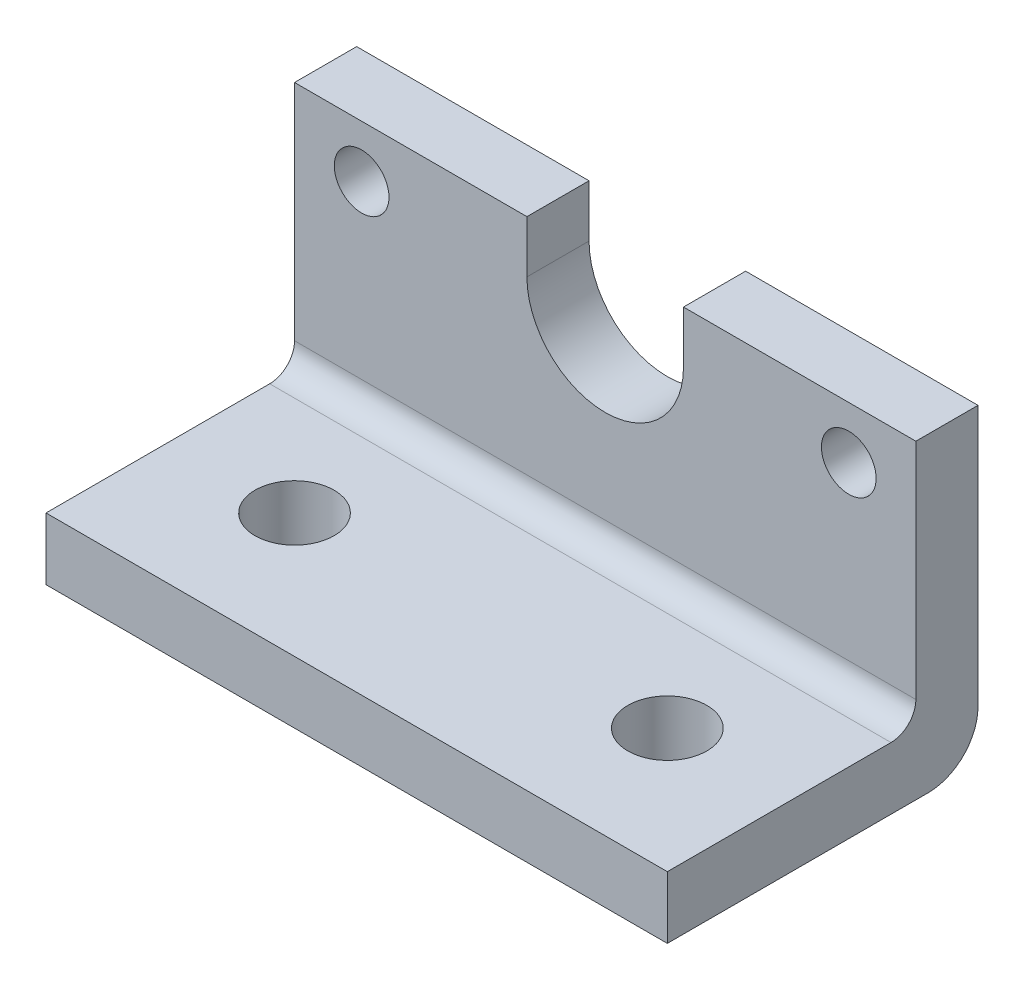
SolidWorks part; units mm, degrees
ref_plane "Front Plane" through (0, 0, 0) normal (0, 0, 1) x (1, 0, 0)
ref_plane "Top Plane" through (0, 0, 0) normal (0, 1, 0) x (1, 0, 0)
ref_plane "Right Plane" through (0, 0, 0) normal (1, 0, 0) x (0, 0, -1)
sketch "Sketch1" plane through (0, 0, 0) normal (0, 0, 1) x (1, 0, 0)
  line L0 (-4.0005, 13.208) -> (-4.0005, 15.875)
  line L1 (-15.875, 15.875) -> (-4.0005, 15.875)
  line L2 (-15.875, 15.875) -> (-15.875, 0)
  line L3 (-15.875, 0) -> (15.875, 0)
  line L4 (15.875, 15.875) -> (15.875, 0)
  line L5 (-15.875, 15.875) -> (15.875, 0) construction
  line L6 (-15.875, 0) -> (15.875, 15.875) construction
  line L7 (4.0005, 13.208) -> (4.0005, 15.875)
  line L8 (0, 13.208) -> (0, 23.3212) construction
  line L9 (4.0005, 15.875) -> (15.875, 15.875)
  arc A0 (-4.0005, 13.208) -> (4.0005, 13.208) centre (0, 13.208) ccw
  circle A1 centre (12.446, 13.208) radius 1.397
  circle A2 centre (-12.446, 13.208) radius 1.397
  point P0 (0, 7.9375)
  dimension "D3" = 8.001
  dimension "D5" = 2.794
  dimension "D1" = 31.75
  dimension "D2" = 15.875
  dimension "D4" = 13.208
  dimension "D6" = 24.892
extrude "Boss-Extrude1" add sketch "Sketch1" against normal blind 3.175
sketch "Sketch2" plane through (0, 0, 0) normal (0, 1, 0) x (1, 0, 0)
  line L0 (0, -12.7) -> (0, 0) construction
  line L1 (-15.875, -12.7) -> (15.875, -12.7)
  line L2 (-15.875, -12.7) -> (-15.875, 0)
  line L3 (-15.875, 0) -> (15.875, 0)
  line L4 (15.875, -12.7) -> (15.875, 0)
  line L5 (-15.875, -12.7) -> (15.875, 0) construction
  line L6 (-15.875, 0) -> (15.875, -12.7) construction
  circle A0 centre (-9.525, -6.35) radius 2.0193
  circle A1 centre (9.525, -6.35) radius 2.0193
  point P0 (0, -6.35)
  dimension "D2" = 4.0386
  dimension "D1" = 12.7
  dimension "D3" = 19.05
extrude "Boss-Extrude2" add sketch "Sketch2" along normal blind 3.175
fillet "Fillet1" radius 1.27 1 edges
fillet "Fillet2" radius 2.54 1 edges at (0, 0, -3.175)
